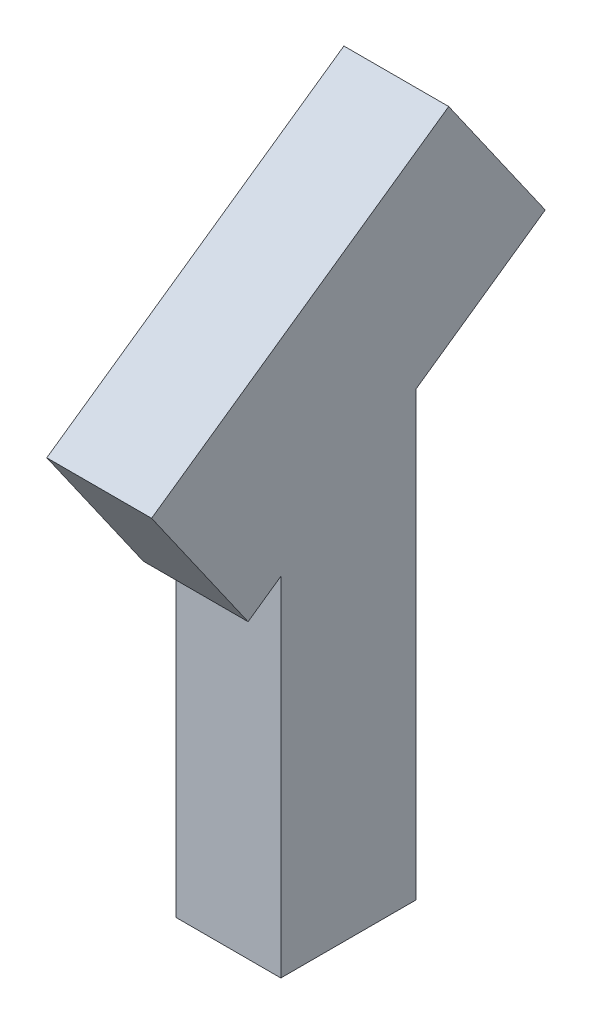
SolidWorks part; units mm, degrees
ref_plane "Front Plane" through (0, 0, 0) normal (0, 0, 1) x (1, 0, 0)
ref_plane "Top Plane" through (0, 0, 0) normal (0, 1, 0) x (1, 0, 0)
ref_plane "Right Plane" through (0, 0, 0) normal (1, 0, 0) x (0, 0, -1)
sketch "Sketch1" plane through (0, 0, 0) normal (1, 0, 0) x (0, 0, -1)
  line L0 (0, 361) -> (0, 0) construction
  line L1 (117.5646, 443.3196) -> (-114.7946, 280.62) construction
  line L2 (-69.2501, 459.8994) -> (38.3634, 306.2114) construction
  line L3 (-49, 0) -> (49, 0)
  line L4 (49, 0) -> (49, 320.8429)
  line L5 (49, 320.8429) -> (142.7067, 386.457)
  line L6 (142.7067, 386.457) -> (72.7303, 486.3936)
  line L7 (72.7303, 486.3936) -> (-142.7067, 335.543)
  line L8 (-142.7067, 335.543) -> (-72.7303, 235.6064)
  line L9 (-49, 0) -> (-49, 252.2226)
  line L10 (-49, 252.2226) -> (-72.7303, 235.6064)
  line L15 (-97.0334, 327.8486) -> (97.0334, 394.1514) construction
  line L16 (64.3395, 440.8431) -> (-64.3395, 281.1569) construction
  point P15 (-97.0334, 327.8486)
  point P16 (0, 0)
  point P17 (0, 0)
  point P22 (0, 0)
  point P23 (0, 0)
  point P24 (97.0334, 394.1514)
  point P25 (0, 0)
  point P26 (0, 0)
  point P27 (0, 0)
  point P28 (0, 0)
  point P29 (0, 0)
  dimension "D1" = 361
  dimension "D2" = 197
  dimension "D3" = 35
  dimension "D4" = 122
  dimension "D5" = 263
  dimension "D6" = 98
  dimension "D7" = 57
sketch "Sketch5" plane through (0, 0, 0) normal (1, 0, 0) x (0, 0, -1)
  line L0 (-97.0334, 327.8486) -> (-64.3395, 281.1569)
  line L1 (-64.3395, 281.1569) -> (97.0334, 394.1514)
  line L2 (-97.0334, 327.8486) -> (64.3395, 440.8431)
  line L3 (64.3395, 440.8431) -> (97.0334, 394.1514)
extrude "Boss-Extrude3" add sketch "Sketch1" along normal mid plane 76
sketch "Sketch7" plane through (0, 0, 0) normal (0, 1, 0) x (1, 0, 0)
  line L0 (-77.3907, 98.3747) -> (77.3907, 98.3747) construction
  line L1 (0, -64.3395) -> (0, 97.0334) construction
  point P2 (0, 98.3747)
